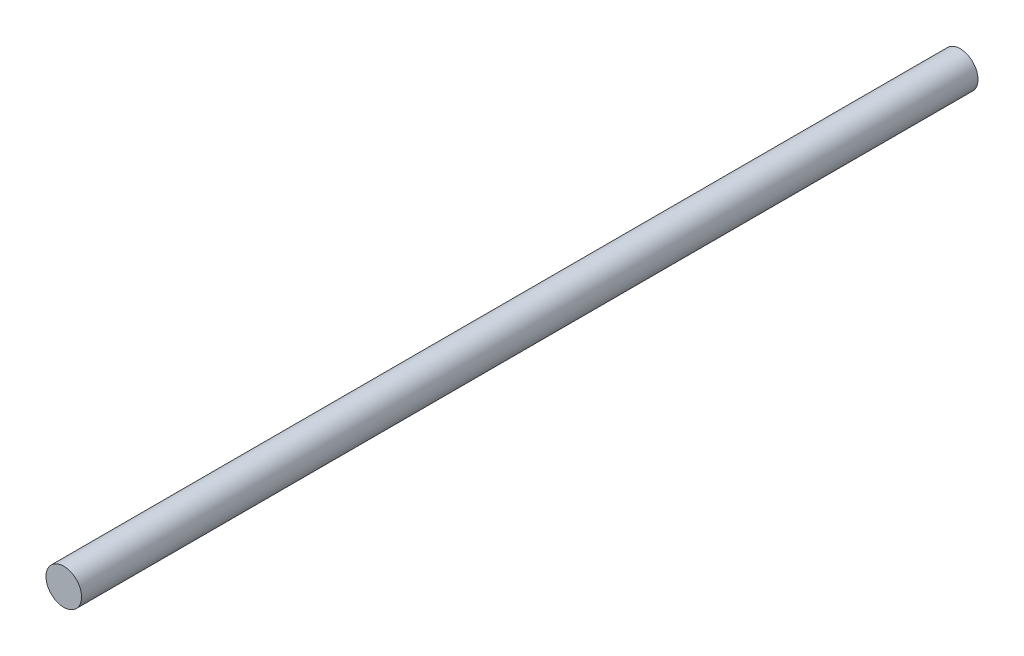
SolidWorks part; units mm, degrees
ref_plane "前视基准面" through (0, 0, 0) normal (0, 0, 1) x (1, 0, 0)
ref_plane "上视基准面" through (0, 0, 0) normal (0, 1, 0) x (1, 0, 0)
ref_plane "右视基准面" through (0, 0, 0) normal (1, 0, 0) x (0, 0, -1)
other "Configuration Table"
sketch "草图1" plane through (0, 0, 0) normal (0, 0, 1) x (1, 0, 0)
  circle A0 centre (0, 0) radius 3
  dimension "D1" = 6
extrude "凸台-拉伸1" add sketch "草图1" along normal blind 151
